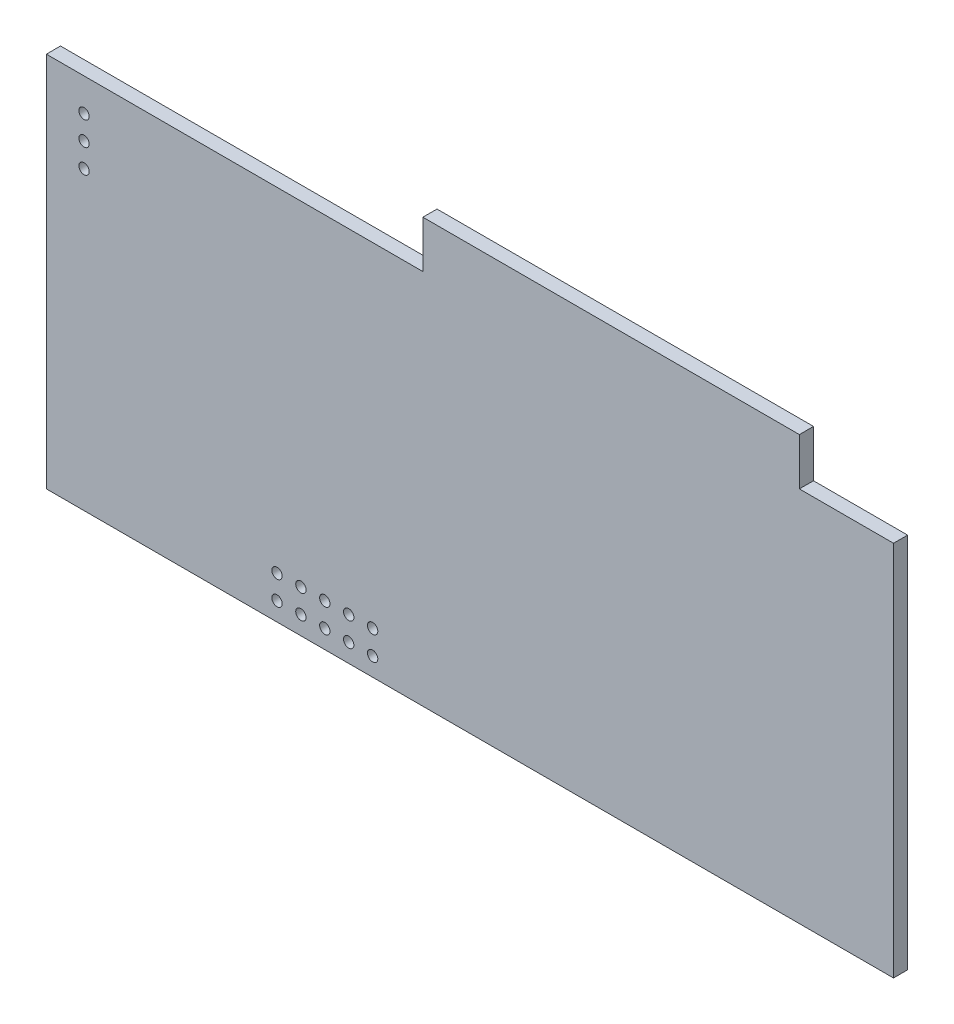
SolidWorks part; units mm, degrees
ref_plane "Спереди" through (0, 0, 0) normal (0, 0, 1) x (1, 0, 0)
ref_plane "Сверху" through (0, 0, 0) normal (0, 1, 0) x (1, 0, 0)
ref_plane "Справа" through (0, 0, 0) normal (1, 0, 0) x (0, 0, -1)
sketch "Эскиз1" plane through (0, 0, 0) normal (0, 0, 1) x (1, 0, 0)
  line L0 (0, 20) -> (0, 25)
  line L1 (-40, -20) -> (50, -20)
  line L2 (-40, -20) -> (-40, 20)
  line L3 (-40, 20) -> (0, 20)
  line L4 (50, -20) -> (50, 20)
  line L5 (0, 25) -> (40, 25)
  line L6 (40, 25) -> (40, 20)
  line L7 (40, 20) -> (50, 20)
  dimension "D1" = 90
  dimension "D2" = 40
  dimension "D3" = 40
  dimension "D4" = 40
  dimension "D5" = 5
  dimension "D6" = 20
extrude "Вытянуть1" add sketch "Эскиз1" along normal blind 1.5
sketch "Эскиз2" plane through (0, 0, 1.5) normal (0, 0, 1) x (1, 0, 0)
  line L0 (-40, 20) -> (-40, -20) construction
  line L1 (-40, -20) -> (50, -20) construction
  circle A0 centre (-36, 16.54) radius 0.55
  circle A1 centre (-36, 11.46) radius 0.55
  circle A2 centre (-36, 14) radius 0.55
  circle A3 centre (-15.5, -15.5) radius 0.55
  circle A4 centre (-15.5, -18.04) radius 0.55
  circle A5 centre (-12.96, -15.5) radius 0.55
  circle A6 centre (-12.96, -18.04) radius 0.55
  circle A7 centre (-10.42, -15.5) radius 0.55
  circle A8 centre (-10.42, -18.04) radius 0.55
  circle A9 centre (-7.88, -15.5) radius 0.55
  circle A10 centre (-7.88, -18.04) radius 0.55
  circle A11 centre (-5.34, -15.5) radius 0.55
  circle A12 centre (-5.34, -18.04) radius 0.55
  dimension "D1" = 5.08
  dimension "D3" = 36.54
  dimension "D4" = 1.1
  dimension "D5" = 2.54
  dimension "D8" = 1.1
  dimension "D9" = 2.54
  dimension "D2" = 4
  dimension "D6" = 4.5
  dimension "D7" = 24.5
  dimension "D10" = 24.5
extrude "Вырез-Вытянуть1" cut sketch "Эскиз2" against normal blind 1.5
